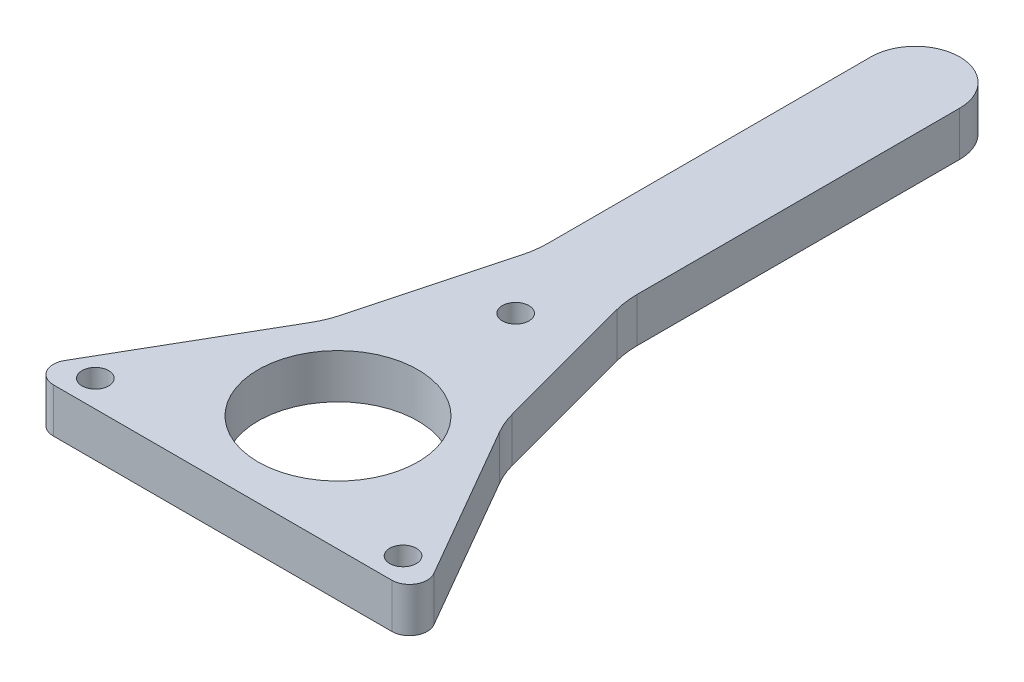
SolidWorks part; units mm, degrees
ref_plane "前视基准面" through (0, 0, 0) normal (0, 0, 1) x (1, 0, 0)
ref_plane "上视基准面" through (0, 0, 0) normal (0, 1, 0) x (1, 0, 0)
ref_plane "右视基准面" through (0, 0, 0) normal (1, 0, 0) x (0, 0, -1)
other "Configuration Table"
sketch "草图1" plane through (0, 0, 0) normal (0, 1, 0) x (1, 0, 0)
  line L0 (0, 26) -> (-22.5167, -13)
  line L1 (-22.5167, -13) -> (22.5167, -13)
  line L2 (22.5167, -13) -> (0, 26)
  line L3 (-22.5167, -13) -> (0, 0) construction
  line L4 (0, 0) -> (0, 26) construction
  line L5 (0, 0) -> (22.5167, -13) construction
  line L6 (0, 0) -> (0, 65) construction
  line L9 (-5, 0) -> (-5, 65)
  line L10 (5, 0) -> (5, 65)
  circle A0 centre (0, 0) radius 20 construction
  circle A1 centre (0, 20) radius 1.5
  circle A2 centre (17.3205, -10) radius 1.5
  circle A3 centre (-17.3205, -10) radius 1.5
  circle A6 centre (0, 0) radius 9
  arc A7 (-5, 0) -> (5, 0) centre (0, 0) ccw
  arc A8 (5, 65) -> (-5, 65) centre (0, 65) ccw
  point P7 (0, 32.5)
  point P12 (0, 0)
  dimension "D1" = 40
  dimension "D3" = 3
  dimension "D7" = 18
  dimension "D5" = 5
  dimension "D4" = 26
  dimension "D6" = 65
  dimension "D2" = 3
extrude "凸台-拉伸1" add sketch "草图1" along normal blind 5 contours A6 L9 L1 L2 L0 L10 A3 A2 A1 | A6 L10 L1 L9 | L10 A8 L9 L1
fillet "圆角1" radius 2 2 edges at (-22.5167, 2.5, 13) (22.5167, 2.5, 13)
chamfer "倒角1" distance 10 2 edges at (5, 2.5, -17.3397) (-5, 2.5, -17.3397)
fillet "圆角3" radius 10 4 edges at (5, 2.5, -27.3397) (10, 2.5, -8.6795) (-10, 2.5, -8.6795) (-5, 2.5, -27.3397)
